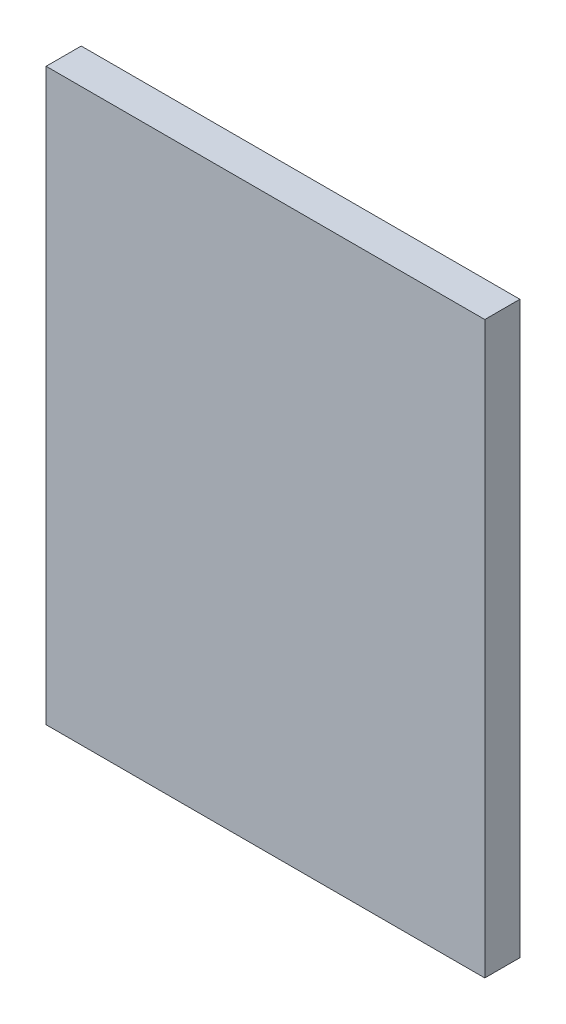
SolidWorks part; units mm, degrees
ref_plane "Ön Düzlem" through (0, 0, 0) normal (0, 0, 1) x (1, 0, 0)
ref_plane "Üst Düzlem" through (0, 0, 0) normal (0, 1, 0) x (1, 0, 0)
ref_plane "Sağ Düzlem" through (0, 0, 0) normal (1, 0, 0) x (0, 0, -1)
sketch "Sketch1" plane through (0, 0, 0) normal (0, 0, 1) x (1, 0, 0)
  line L0 (0, 0) -> (100, 0)
  line L1 (0, 0) -> (0, 130)
  line L2 (100, 0) -> (100, 130)
  line L3 (0, 130) -> (100, 130)
  dimension "D1" = 130
  dimension "D2" = 100
extrude "Boss-Extrude1" add sketch "Sketch1" along normal blind 8
